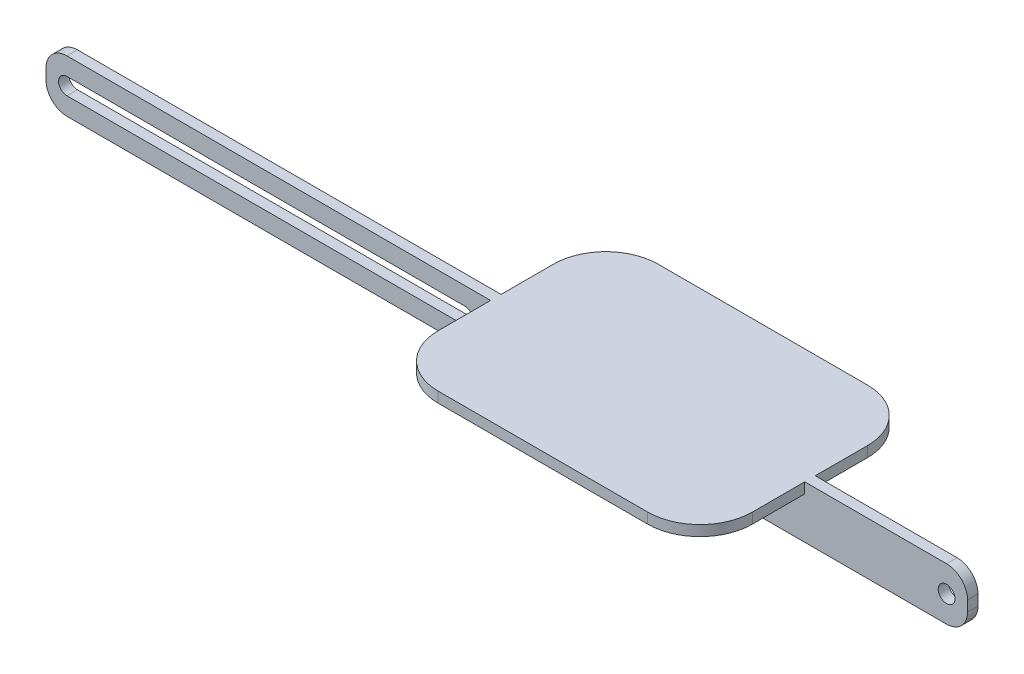
SolidWorks part; units mm, degrees
ref_plane "Front Plane" through (0, 0, 0) normal (0, 0, 1) x (1, 0, 0)
ref_plane "Top Plane" through (0, 0, 0) normal (0, 1, 0) x (1, 0, 0)
ref_plane "Right Plane" through (0, 0, 0) normal (1, 0, 0) x (0, 0, -1)
sketch "Sketch1" plane through (0, 0, 0) normal (0, 0, 1) x (1, 0, 0)
  line L0 (-376.6667, 0) -> (-283.236, 0) construction
  line L1 (-366.6667, 12.5) -> (-126.6667, 12.5)
  line L2 (-376.6667, 2.5) -> (-376.6667, -2.5)
  line L3 (-366.6667, -12.5) -> (-126.6667, -12.5)
  line L4 (63.3333, 2.5) -> (63.3333, -2.5)
  line L5 (-376.6667, 12.5) -> (-369.0935, 12.2011) construction
  line L7 (-126.6667, 12.5) -> (-126.6667, -62.445) construction
  line L8 (-366.6667, 4) -> (-176.6667, 4)
  line L9 (-366.6667, -4) -> (-176.6667, -4)
  line L10 (-126.6667, 12.5) -> (53.3333, 12.5)
  line L14 (-126.6667, -12.5) -> (53.3333, -12.5)
  arc A0 (-366.6667, 4) -> (-366.6667, -4) centre (-366.6667, 0) ccw
  arc A1 (-376.6667, -2.5) -> (-366.6667, -12.5) centre (-366.6667, -2.5) ccw
  arc A2 (-376.6667, 2.5) -> (-366.6667, 12.5) centre (-366.6667, 2.5) cw
  arc A3 (63.3333, -2.5) -> (53.3333, -12.5) centre (53.3333, -2.5) cw
  arc A4 (63.3333, 2.5) -> (53.3333, 12.5) centre (53.3333, 2.5) ccw
  circle A5 centre (53.3333, 0) radius 4
  arc A6 (-176.6667, -4) -> (-176.6667, 4) centre (-176.6667, 0) ccw
  point P0 (0, 0)
  dimension "D3" = 8
  dimension "D5" = 10
  dimension "D4" = 10
  dimension "D6" = 190
extrude "Boss-Extrude1" add sketch "Sketch1" along normal blind 5
sketch "Sketch2" plane through (0, 0, 5) normal (0, 0, 1) x (1, 0, 0)
  line L5 (0, 0) -> (-188.2995, 0) construction
  line L6 (-14.3899, 12.5) -> (-14.3899, 7.5)
  line L7 (-164.3899, 7.5) -> (-14.3899, 7.5)
  line L8 (-164.3899, 12.5) -> (-164.3899, 7.5)
  line L9 (-164.3899, 12.5) -> (-14.3899, 12.5)
extrude "Boss-Extrude2" add sketch "Sketch2" along normal blind 50 and the other way blind 55
fillet "Fillet1" radius 25 4 edges at (-164.3899, 10, 55) (-14.3899, 10, 55) (-164.3899, 10, -50) (-14.3899, 10, -50)
